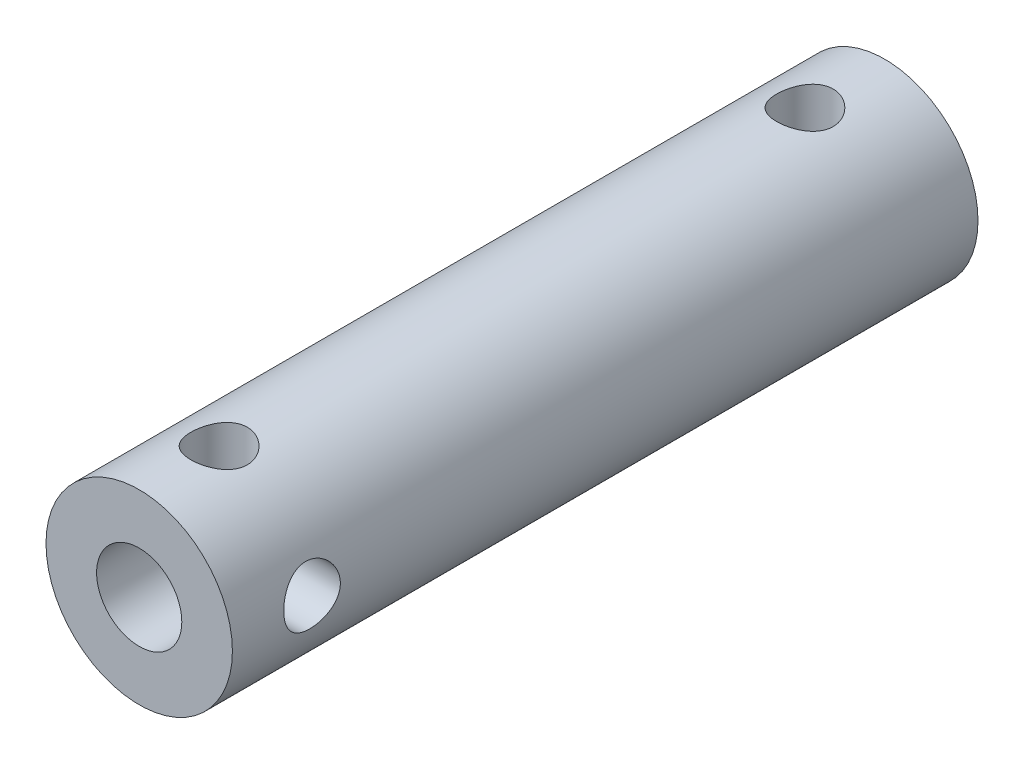
SolidWorks part; units mm, degrees
ref_plane "Front" through (0, 0, 0) normal (0, 0, 1) x (1, 0, 0)
ref_plane "Top" through (0, 0, 0) normal (0, 1, 0) x (1, 0, 0)
ref_plane "Right" through (0, 0, 0) normal (1, 0, 0) x (0, 0, -1)
sketch "Sketch1" plane through (0, 0, 0) normal (0, 0, 1) x (1, 0, 0)
  circle A0 centre (0, 0) radius 11.1125
  circle A1 centre (0, 0) radius 5.08
  dimension "D1" = 22.225
  dimension "D2" = 10.16
extrude "Boss-Extrude1" add sketch "Sketch1" along normal blind 88.9
sketch "Sketch2" plane through (0, 0, 0) normal (0, 1, 0) x (1, 0, 0)
  line L0 (0, 0) -> (0, -114.778) construction
  line L1 (-11.1125, -88.9) -> (11.1125, -88.9) construction
  line L2 (11.1125, 0) -> (-11.1125, 0) construction
  circle A0 centre (0, -79.375) radius 3.3655
  circle A1 centre (0, -9.525) radius 3.3655
  dimension "D1" = 6.731
  dimension "D2" = 9.525
  dimension "D3" = 9.525
extrude "Cut-Extrude1" cut sketch "Sketch2" against normal through all and the other way through all
chamfer "Chamfer1" [suppressed] distance 1.27 angle 60
sketch "Sketch4" plane through (0, 0, 0) normal (1, 0, 0) x (0, 0, -1)
  line L0 (-88.9, 5.08) -> (-88.9, -5.08) construction
  circle A0 centre (-79.375, 0.7354) radius 3.3655
  dimension "D1" = 9.525
extrude "Cut-Extrude2" cut sketch "Sketch4" against normal through all and the other way through all
